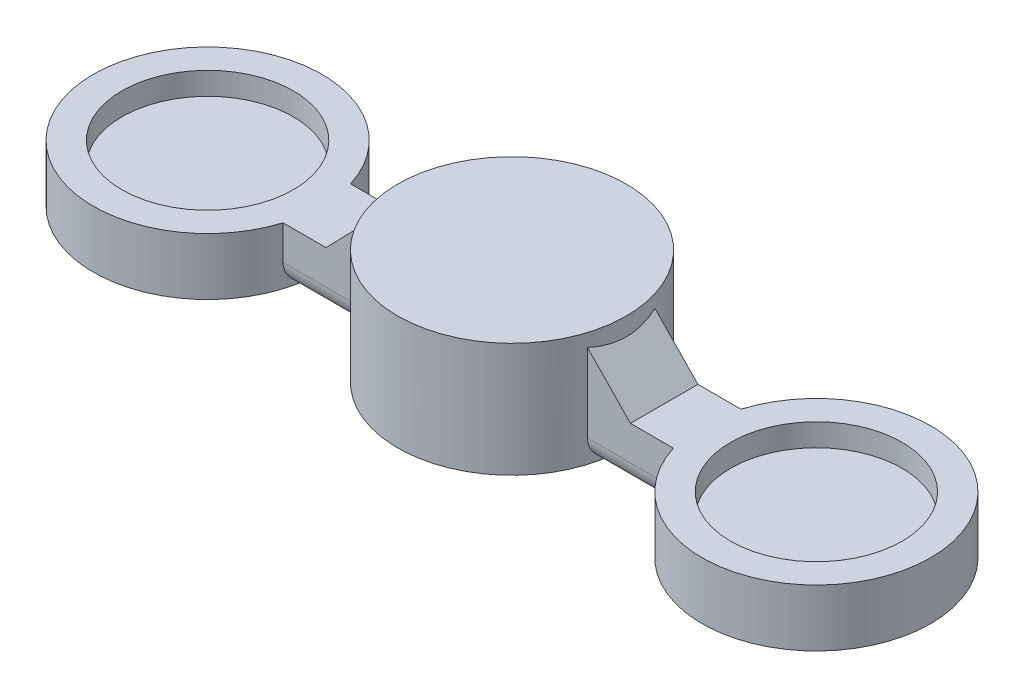
SolidWorks part; units mm, degrees
ref_plane "Front Plane" through (0, 0, 0) normal (0, 0, 1) x (1, 0, 0)
ref_plane "Top Plane" through (0, 0, 0) normal (0, 1, 0) x (1, 0, 0)
ref_plane "Right Plane" through (0, 0, 0) normal (1, 0, 0) x (0, 0, -1)
sketch "Sketch1" plane through (0, 0, 0) normal (0, 1, 0) x (1, 0, 0)
  circle A0 centre (0, 0) radius 12.7
  dimension "D1" = 25.4
extrude "Boss-Extrude1" add sketch "Sketch1" along normal blind 6.35
sketch "Sketch2" plane through (0, 6.35, 0) normal (0, 1, 0) x (1, 0, 0)
  line L1 (38.1, -3.75) -> (-38.1, -3.75)
  line L2 (38.1, -3.75) -> (38.1, 3.75)
  line L3 (38.1, 3.75) -> (-38.1, 3.75)
  line L4 (-38.1, -3.75) -> (-38.1, 3.75)
  line L5 (38.1, -3.75) -> (-38.1, 3.75) construction
  line L6 (38.1, 3.75) -> (-38.1, -3.75) construction
  point P0 (0, 0)
  dimension "D1" = 7.5
  dimension "D2" = 76.2
extrude "Boss-Extrude2" add sketch "Sketch2" against normal up to surface (6.35 mm away) up to face at (0, 0, 12.7)
sketch "Sketch3" plane through (0, 6.35, 0) normal (0, 1, 0) x (1, 0, 0)
  circle A0 centre (-33.8191, 0) radius 12.7
  dimension "D1" = 25.4
extrude "Boss-Extrude3" add sketch "Sketch3" against normal up to surface (6.35 mm away) up to face at (0, 0, 0)
sketch "Sketch4" plane through (0, 6.35, 0) normal (0, 1, 0) x (1, 0, 0)
  circle A0 centre (-33.8191, 0) radius 9.525
  arc A1 (-21.6854, 3.75) -> (-21.6854, -3.75) centre (-33.8191, 0) ccw construction
  dimension "D1" = 19.05
extrude "Cut-Extrude1" cut sketch "Sketch4" against normal blind 2.5
mirror "Mirror1" about plane through (0, 0, 0) normal (1, 0, 0) of "Cut-Extrude1", "Boss-Extrude3"
fillet "Fillet1" radius 2.54 4 edges at (16.9095, 0, 3.75) (-16.9095, 0, 3.75) (-16.9095, 0, -3.75) (16.9095, 0, -3.75)
sketch "Sketch5" plane through (0, 6.35, 0) normal (0, 1, 0) x (1, 0, 0)
  circle A0 centre (0, 0) radius 12.7
extrude "Boss-Extrude4" add sketch "Sketch5" along normal blind 6.35
sketch "Sketch6" plane through (0, 0, -3.75) normal (0, 0, -1) x (-1, 0, 0)
  line L0 (-16.9095, 6.35) -> (-10.7518, 12.7)
  line L1 (-21.6854, 6.35) -> (-12.1337, 6.35) construction
  line L8 (12.7, 12.7) -> (-12.7, 12.7) construction
rib "Rib6" sketch "Sketch6" sketch "Sketch6" thickness 7.5 extrusion direction parallel to sketch draft on no parameters "D1"=7.5
mirror "Mirror2" about plane through (0, 0, 0) normal (1, 0, 0) of "Rib6"
